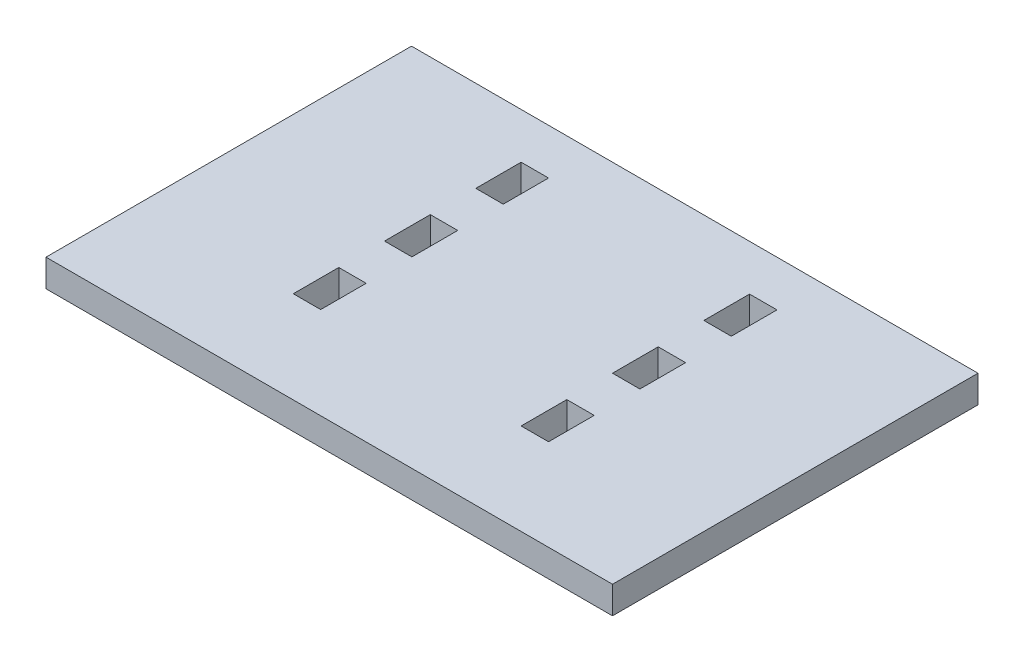
SolidWorks part; units mm, degrees
ref_plane "Front Plane" through (0, 0, 0) normal (0, 0, 1) x (1, 0, 0)
ref_plane "Top Plane" through (0, 0, 0) normal (0, 1, 0) x (1, 0, 0)
ref_plane "Right Plane" through (0, 0, 0) normal (1, 0, 0) x (0, 0, -1)
sketch "Sketch1" plane through (0, 0, 0) normal (0, 1, 0) x (1, 0, 0)
  line L1 (0, 0) -> (22, 0)
  line L2 (0, 0) -> (0, 40)
  line L3 (0, 40) -> (22, 40)
  line L4 (22, 0) -> (22, 40)
  line L5 (0, 40) -> (-20, 40)
  line L6 (0, 40) -> (0, 0)
  line L7 (0, 0) -> (-20, 0)
  line L8 (-20, 40) -> (-20, 0)
  line L9 (22, 40) -> (42, 40)
  line L10 (22, 40) -> (22, 0)
  line L11 (22, 0) -> (42, 0)
  line L12 (42, 40) -> (42, 0)
  line L20 (11, 40) -> (11, 0) construction
  line L21 (0, 35) -> (-3, 35)
  line L22 (0, 35) -> (0, 30.0397)
  line L23 (0, 30.0397) -> (-3, 30.0397)
  line L24 (-3, 35) -> (-3, 30.0397)
  line L29 (0, 25.0602) -> (-3, 25.0602)
  line L30 (0, 25.0602) -> (0, 20.0457)
  line L31 (0, 20.0457) -> (-3, 20.0457)
  line L32 (-3, 25.0602) -> (-3, 20.0457)
  line L37 (0, 15.0419) -> (-3, 15.0419)
  line L38 (0, 15.0419) -> (0, 10.0628)
  line L39 (0, 10.0628) -> (-3, 10.0628)
  line L40 (-3, 15.0419) -> (-3, 10.0628)
  line L54 (22, 35) -> (24.9981, 35)
  line L55 (22, 35) -> (22, 30)
  line L56 (22, 30) -> (24.9981, 30)
  line L57 (24.9981, 35) -> (24.9981, 30)
  line L62 (22, 25) -> (24.9981, 25)
  line L63 (22, 25) -> (22, 20)
  line L64 (22, 20) -> (24.9981, 20)
  line L65 (24.9981, 25) -> (24.9981, 20)
  line L70 (22, 15) -> (24.9981, 15)
  line L71 (22, 15) -> (22, 10)
  line L72 (22, 10) -> (24.9981, 10)
  line L73 (24.9981, 15) -> (24.9981, 10)
  dimension "D1" = 22
  dimension "D2" = 40
  dimension "D3" = 20
  dimension "D4" = 20
  dimension "D5" = 3
  dimension "D9" = 5
  dimension "D11" = 5
  dimension "D12" = 5
  dimension "D13" = 5
extrude "Boss-Extrude1" add sketch "Sketch1" along normal blind 3 contours L20 L3 L6 L2 L1 | L40 L37 L6 L31 L32 L29 L23 L24 L21 L5 L8 L7 L2 L39 | L3 L20 L1 L4 L10 | L70 L73 L72 L4 L11 L12 L9 L10 L54 L57 L56 L62 L65 L64
